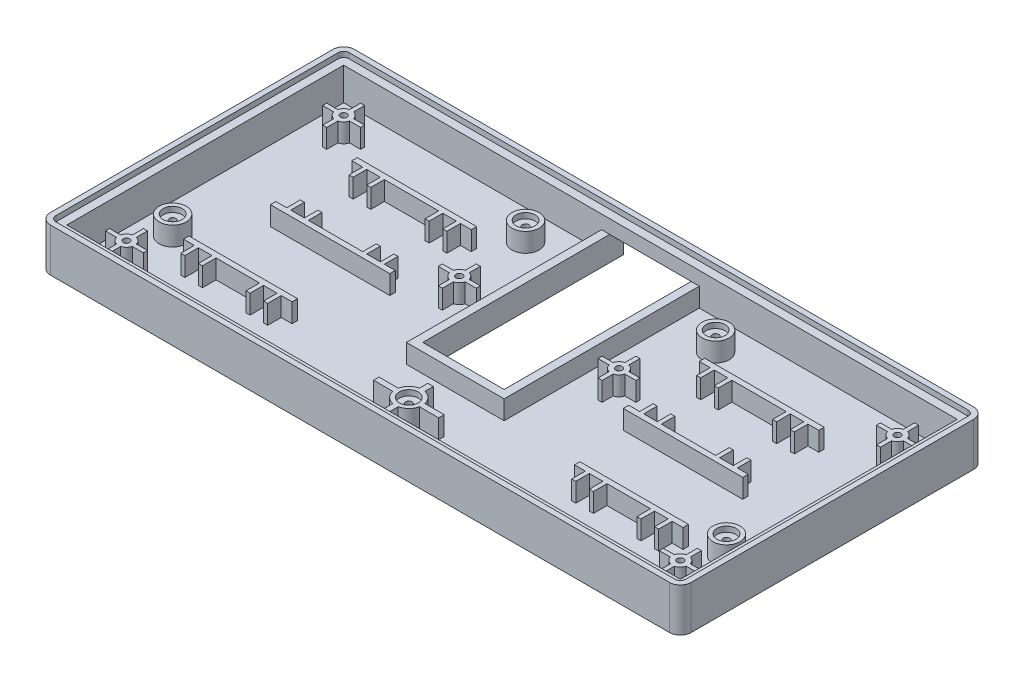
SolidWorks part; units mm, degrees
ref_plane "Front Plane" through (0, 0, 0) normal (0, 0, 1) x (1, 0, 0)
ref_plane "Top Plane" through (0, 0, 0) normal (0, 1, 0) x (1, 0, 0)
ref_plane "Right Plane" through (0, 0, 0) normal (1, 0, 0) x (0, 0, -1)
sketch "Sketch2" plane through (0, 0, 0) normal (0, 1, 0) x (1, 0, 0)
  line L0 (0, -55) -> (0, 55) construction
  line L1 (-118, 56) -> (118, 56)
  line L2 (-118, 56) -> (-118, -56)
  line L3 (-118, -56) -> (118, -56)
  line L4 (118, 56) -> (118, -56)
  line L5 (-55, 0) -> (55, 0) construction
  dimension "D1" = 236
  dimension "D2" = 112
  dimension "D3" = 118
  dimension "D4" = 56
extrude "Boss-Extrude1" add sketch "Sketch2" along normal blind 16
sketch "Sketch3" plane through (0, 16, 0) normal (0, 1, 0) x (1, 0, 0)
  line L0 (0, -55) -> (0, 55) construction
  line L1 (-113, 51) -> (113, 51)
  line L2 (-113, 51) -> (-113, -51)
  line L3 (-113, -51) -> (113, -51)
  line L4 (113, 51) -> (113, -51)
  line L5 (-9.35, 0) -> (9.35, 0) construction
  dimension "D1" = 102
  dimension "D2" = 226
  dimension "D3" = 113
  dimension "D4" = 51
extrude "PCB_case" cut sketch "Sketch3" against normal blind 14
sketch "Sketch4" plane through (0, 16, 0) normal (0, 1, 0) x (1, 0, 0)
  line L0 (-9.35, 0) -> (9.35, 0) construction
  line L1 (-116, 54) -> (116, 54)
  line L2 (-116, 54) -> (-116, -54)
  line L3 (-116, -54) -> (116, -54)
  line L4 (116, 54) -> (116, -54)
  line L5 (0, -8.8) -> (0, 8.8) construction
  dimension "D1" = 232
  dimension "D2" = 108
  dimension "D3" = 54
  dimension "D4" = 116
extrude "Upper_case" cut sketch "Sketch4" against normal blind 2
fillet "Fillet_Outside" radius 4 4 edges at (118, 8, -56) (-118, 8, -56) (-118, 8, 56) (118, 8, 56)
fillet "Fillet_inside_uplayer" radius 2 4 edges at (-116, 15, 54) (116, 15, 54) (116, 15, -54) (-116, 15, -54)
sketch "PCB_position" plane through (0, 0, 0) normal (0, 1, 0) x (1, 0, 0)
  line L1 (112, -50) -> (-112, -50)
  line L2 (112, -50) -> (112, 50)
  line L3 (112, 50) -> (-112, 50)
  line L4 (-112, -50) -> (-112, 50)
  line L5 (112, -50) -> (-112, 50) construction
  line L6 (112, 50) -> (-112, -50) construction
  point P0 (0, 0)
  dimension "D1" = 224
  dimension "D2" = 100
sketch "Ardino_pro_micro" plane through (0, 0, 0) normal (0, 1, 0) x (1, 0, 0)
  line L0 (0, -7.15) -> (0, 7.15) construction
  line L1 (-9, 25) -> (9, 25)
  line L2 (-9, 25) -> (-9, -11.9)
  line L3 (-9, -11.9) -> (9, -11.9)
  line L4 (9, 25) -> (9, -11.9)
  line L5 (112, 50) -> (-112, 50) construction
  dimension "D1" = 18
  dimension "D2" = 36.9
  dimension "D3" = 9
  dimension "D4" = 25
sketch "Sketch6" plane through (0, 0, 0) normal (0, 1, 0) x (1, 0, 0)
  circle A0 centre (0, -38) radius 5
  dimension "D1" = 10
extrude "Boss-Extrude2" add sketch "Sketch6" along normal blind 9
sketch "Sketch45" plane through (0, 0, 0) normal (0, 1, 0) x (1, 0, 0)
  line L0 (-12, -37) -> (-1, -37)
  line L1 (-1, -37) -> (-1, -30)
  line L2 (-1, -30) -> (1, -30)
  line L3 (1, -30) -> (1, -37)
  line L4 (1, -37) -> (12, -37)
  line L5 (12, -37) -> (12, -39)
  line L6 (12, -39) -> (1, -39)
  line L7 (1, -39) -> (1, -46)
  line L8 (1, -46) -> (-1, -46)
  line L9 (-1, -46) -> (-1, -39)
  line L10 (-1, -39) -> (-12, -39)
  line L11 (-12, -37) -> (-12, -39)
  line L12 (-12, -38) -> (12, -38) construction
  line L13 (0, -30) -> (0, -46) construction
  point P16 (0, -38)
  dimension "D1" = 2
  dimension "D2" = 2
  dimension "D3" = 8
  dimension "D4" = 12
extrude "Boss-Extrude6" add sketch "Sketch45" along normal blind 9
ref_plane "PCB_bot" through (0, 9, 0) normal (0, 1, 0) x (1, 0, 0)
sketch "Sketch27" plane through (0, 9, 0) normal (0, 1, 0) x (1, 0, 0)
  circle A0 centre (0, -38) radius 3.5
  dimension "D1" = 7
extrude "Cut-Extrude1" cut sketch "Sketch27" against normal blind 2
sketch "Sketch28" plane through (0, 0, 0) normal (0, 1, 0) x (1, 0, 0)
  line L0 (112, 50) -> (-112, 50) construction
  circle A0 centre (-35, 40) radius 5
  dimension "D1" = 10
  dimension "D2" = 10
extrude "Boss-Extrude3" add sketch "Sketch28" along normal blind 9
sketch "Sketch29" plane through (0, 9, 0) normal (0, 1, 0) x (1, 0, 0)
  circle A0 centre (-35, 40) radius 3.5
  dimension "D1" = 7
extrude "Cut-Extrude3" cut sketch "Sketch29" against normal blind 2
mirror "Mirror7" about plane through (0, 0, 0) normal (1, 0, 0) of "Cut-Extrude3", "Boss-Extrude3"
sketch "Sketch43" plane through (0, 0, 0) normal (0, 1, 0) x (1, 0, 0)
  point P0 (-35, 40)
  point P3 (35, 40)
  point P6 (0, -38)
hole_wizard "M2 Clearance Hole3" positions "Sketch43" profile "Sketch42" hole size "M2" standard "ANSI Metric" end condition through all
sketch "Sketch42" plane through (-35, 0, -40) normal (1, 0, 0) x (0, 0, -1)
  line L0 (0, 0) -> (0, 16)
  line L1 (0, 16) -> (1.2, 16)
  line L2 (1.2, 16) -> (1.2, 0)
  line L5 (1.2, 0) -> (0, 0)
  line L11 (0, -6.35) -> (0, 107.95) construction
  dimension "Thru Hole Dia." = 2.4
  dimension "Thru Hole Depth" = 16
sketch "Sketch44" plane through (0, 0, 0) normal (0, 1, 0) x (1, 0, 0)
  line L4 (-112, -50) -> (-112, 50) construction
  line L5 (112, -50) -> (-112, -50) construction
  circle A0 centre (-102, -23) radius 5
  dimension "D1" = 10
  dimension "D2" = 10
  dimension "D3" = 27
extrude "Boss-Extrude5" add sketch "Sketch44" along normal blind 9
sketch "Sketch46" plane through (0, 9, 0) normal (0, 1, 0) x (1, 0, 0)
  circle A0 centre (-102, -23) radius 3.5
  dimension "D1" = 7
extrude "Cut-Extrude6" cut sketch "Sketch46" against normal blind 2
sketch "Sketch49" plane through (0, 0, 0) normal (0, 1, 0) x (1, 0, 0)
  point P0 (-102, -23)
hole_wizard "M2 Clearance Hole4" positions "Sketch49" profile "Sketch48" hole size "M2" standard "ANSI Metric" end condition through all
sketch "Sketch48" plane through (-102, 0, 23) normal (1, 0, 0) x (0, 0, -1)
  line L0 (0, 0) -> (0, 16)
  line L1 (0, 16) -> (1.2, 16)
  line L2 (1.2, 16) -> (1.2, 0)
  line L5 (1.2, 0) -> (0, 0)
  line L11 (0, -6.35) -> (0, 107.95) construction
  dimension "Thru Hole Dia." = 2.4
  dimension "Thru Hole Depth" = 16
sketch "Sketch10" plane through (0, 0, 0) normal (0, 1, 0) x (1, 0, 0)
  line L0 (-86, 29) -> (-42, 29)
  line L1 (-42, 29) -> (-42, 27)
  line L3 (-86, 27) -> (-86, 29)
  line L4 (-74, 27) -> (-74, 22)
  line L5 (-74, 22) -> (-75.5, 22)
  line L6 (-75.5, 22) -> (-75.5, 27)
  line L8 (-54, 27) -> (-54, 22)
  line L9 (-54, 22) -> (-52.5, 22)
  line L10 (-52.5, 22) -> (-52.5, 27)
  line L11 (-47.5, 27) -> (-47.5, 22)
  line L12 (-47.5, 22) -> (-46, 22)
  line L13 (-46, 22) -> (-46, 27)
  line L14 (-80.5, 27) -> (-80.5, 22)
  line L15 (-80.5, 22) -> (-82, 22)
  line L16 (-82, 22) -> (-82, 27)
  line L18 (-112, -50) -> (-112, 50) construction
  line L25 (-86, 27) -> (-82, 27)
  line L26 (-80.5, 27) -> (-75.5, 27)
  line L27 (-74, 27) -> (-54, 27)
  line L28 (-52.5, 27) -> (-47.5, 27)
  line L29 (-46, 27) -> (-42, 27)
  line L30 (-75.5, 20) -> (-53.5, 20) construction
  dimension "D1" = 2
  dimension "D2" = 26
  dimension "D3" = 44
  dimension "D4" = 20
  dimension "D5" = 1.5
  dimension "D6" = 5
  dimension "D7" = 7
  dimension "D8" = 5
  dimension "D10" = 5
extrude "PCB_Sup1" add sketch "Sketch10" along normal blind 9
mirror "PCB_Sup2" about plane through (0, 0, 0) normal (1, 0, 0) of "PCB_Sup1"
sketch "Sketch16" plane through (0, 0, 0) normal (0, 1, 0) x (1, 0, 0)
  line L3 (-43, -2) -> (-87, -2)
  line L4 (-87, -2) -> (-87, 0)
  line L5 (-43, 0) -> (-43, -2)
  line L6 (-113, -51) -> (-113, 51) construction
  line L8 (-87, -1) -> (-43, -1) construction
  line L10 (-9.35, 0) -> (9.35, 0) construction
  line L11 (-83, 0) -> (-83, 5)
  line L12 (-83, 5) -> (-81.5, 5)
  line L13 (-81.5, 5) -> (-81.5, 0)
  line L14 (-76.5, 5) -> (-76.5, 0)
  line L15 (-76.5, 5) -> (-75, 5)
  line L16 (-75, 5) -> (-75, 0)
  line L17 (-55, 5) -> (-55, 0)
  line L18 (-53.5, 0) -> (-53.5, 5)
  line L19 (-53.5, 5) -> (-55, 5)
  line L20 (-47, 0) -> (-47, 5)
  line L21 (-47, 5) -> (-48.5, 5)
  line L22 (-48.5, 5) -> (-48.5, 0)
  line L25 (-87, 0) -> (-83, 0)
  line L26 (-81.5, 0) -> (-76.5, 0)
  line L27 (-75, 0) -> (-55, 0)
  line L28 (-53.5, 0) -> (-48.5, 0)
  line L29 (-47, 0) -> (-43, 0)
  point P4 (-87, -1)
  dimension "D1" = 2
  dimension "D2" = 5
  dimension "D3" = 5
  dimension "D4" = 5
  dimension "D5" = 20
  dimension "D6" = 1.5
  dimension "D7" = 1
  dimension "D8" = 44
  dimension "D9" = 26
extrude "PCB_Sup3" add sketch "Sketch16" along normal blind 9
mirror "PCB_Sup4" about plane through (0, 0, 0) normal (1, 0, 0) of "PCB_Sup3"
sketch "Sketch17" plane through (0, 0, 0) normal (0, 1, 0) x (1, 0, 0)
  line L0 (-92, -27) -> (-52, -27)
  line L1 (-52, -27) -> (-52, -29)
  line L2 (-52, -29) -> (-56, -29)
  line L3 (-56, -29) -> (-56, -34)
  line L4 (-56, -34) -> (-57.5, -34)
  line L5 (-57.5, -34) -> (-57.5, -29)
  line L6 (-57.5, -29) -> (-62.5, -29)
  line L7 (-62.5, -29) -> (-62.5, -34)
  line L8 (-62.5, -34) -> (-64, -34)
  line L9 (-64, -34) -> (-64, -29)
  line L10 (-64, -29) -> (-80, -29)
  line L11 (-80, -29) -> (-80, -34)
  line L12 (-80, -34) -> (-81.5, -34)
  line L13 (-81.5, -34) -> (-81.5, -29)
  line L14 (-81.5, -29) -> (-86.5, -29)
  line L15 (-86.5, -29) -> (-86.5, -34)
  line L16 (-86.5, -34) -> (-88, -34)
  line L17 (-88, -34) -> (-88, -29)
  line L18 (-88, -29) -> (-92, -29)
  line L19 (-92, -29) -> (-92, -27)
  line L21 (-112, -50) -> (-112, 50) construction
  line L22 (-92, -28) -> (-52, -28) construction
  line L23 (-9.35, 0) -> (9.35, 0) construction
  dimension "D1" = 2
  dimension "D2" = 1.5
  dimension "D3" = 4
  dimension "D4" = 5
  dimension "D5" = 5
  dimension "D6" = 4
  dimension "D7" = 5
  dimension "D8" = 28
  dimension "D9" = 40
  dimension "D10" = 20
extrude "PCB_Sup5" add sketch "Sketch17" along normal blind 9
mirror "PCB_Sup6" about plane through (0, 0, 0) normal (1, 0, 0) of "PCB_Sup5"
sketch "Sketch20" plane through (0, 0, 0) normal (0, 1, 0) x (1, 0, 0)
  line L0 (-13, 56) -> (-13, -21.9)
  line L1 (-13, -21.9) -> (-14, -21.9)
  line L3 (-14, -3.5) -> (-19, -3.5)
  line L4 (-19, -3.5) -> (-19, -2.5)
  line L5 (-19, -2.5) -> (-14, -2.5)
  line L6 (-14, -2.5) -> (-14, 2.5)
  line L7 (-14, 2.5) -> (-19, 2.5)
  line L8 (-19, 2.5) -> (-19, 3.5)
  line L9 (-19, 3.5) -> (-14, 3.5)
  line L10 (-14, 3.5) -> (-14, 45)
  line L11 (-14, 45) -> (-19, 45)
  line L12 (-19, 45) -> (-19, 46)
  line L13 (-19, 46) -> (-14, 46)
  line L14 (-14, 46) -> (-14, 51)
  line L15 (-14, 51) -> (-19, 51)
  line L16 (-19, 51) -> (-19, 52)
  line L17 (-19, 52) -> (-14, 52)
  line L18 (-14, 52) -> (-14, 56)
  line L19 (-14, 56) -> (-13, 56)
  line L20 (114, 56) -> (-114, 56) construction
  line L21 (-9, -11.9) -> (9, -11.9) construction
  line L26 (-14, -3.5) -> (-14, -10.9)
  line L27 (-14, -10.9) -> (-19, -10.9)
  line L28 (-19, -10.9) -> (-19, -11.9)
  line L29 (-19, -11.9) -> (-14, -11.9)
  line L30 (-14, -11.9) -> (-14, -16.9)
  line L31 (-14, -16.9) -> (-19, -16.9)
  line L32 (-19, -16.9) -> (-19, -17.9)
  line L33 (-19, -17.9) -> (-14, -17.9)
  line L34 (-14, -17.9) -> (-14, -21.9)
  line L35 (-9.35, 0) -> (9.35, 0) construction
  line L36 (-9, 25) -> (-9, -11.9) construction
  point P36 (-14, 0)
  dimension "D1" = 10
  dimension "D3" = 1
  dimension "D4" = 5
  dimension "D5" = 5
  dimension "D6" = 4
  dimension "D7" = 4
  dimension "D8" = 1
  dimension "D9" = 4
sketch "Sketch21" plane through (0, 0, 0) normal (0, 1, 0) x (1, 0, 0)
  line L4 (112, 50) -> (-112, 50) construction
  line L5 (-112, -50) -> (-112, 50) construction
  circle A0 centre (-102, 40) radius 3
  dimension "D1" = 6
  dimension "D2" = 10
  dimension "D3" = 10
extrude "TL_round" add sketch "Sketch21" along normal blind 9
sketch "Sketch22" plane through (0, 0, 0) normal (0, 1, 0) x (1, 0, 0)
  line L0 (-102.75, 47) -> (-102.75, 40.75)
  line L1 (-102.75, 47) -> (-101.25, 47)
  line L3 (-101.25, 33) -> (-102.75, 33)
  line L6 (-95, 40.75) -> (-95, 39.25)
  line L8 (-109, 39.25) -> (-109, 40.75)
  line L9 (-112.6968, 40) -> (-77.0407, 40) construction
  line L10 (-102, 65.5448) -> (-102, 28.4552) construction
  line L11 (-102.75, 40.75) -> (-109, 40.75)
  line L12 (-109, 39.25) -> (-102.75, 39.25)
  line L13 (-102.75, 39.25) -> (-102.75, 33)
  line L14 (-101.25, 33) -> (-101.25, 39.25)
  line L15 (-101.25, 39.25) -> (-95, 39.25)
  line L16 (-95, 40.75) -> (-101.25, 40.75)
  line L17 (-101.25, 40.75) -> (-101.25, 47)
  circle A2 centre (-102, 40) radius 3 construction
  point P15 (-102, 47)
  point P16 (-102, 40)
  point P20 (-109, 40)
  dimension "D1" = 1.5
  dimension "D2" = 1.5
  dimension "D3" = 14
  dimension "D4" = 14
  dimension "D5" = 7
  dimension "D6" = 7
extrude "TL_rect" add sketch "Sketch22" along normal blind 9
sketch "Sketch32" plane through (0, 9, 0) normal (0, 1, 0) x (1, 0, 0)
  point P0 (-102, 40)
hole_wizard "M2 Clearance Hole1" positions "Sketch32" profile "Sketch31" hole size "M2" standard "ANSI Metric" end condition through all
sketch "Sketch31" plane through (-102, 9, -40) normal (1, 0, 0) x (0, 0, 1)
  line L0 (0, 0) -> (0, 9)
  line L1 (0, 9) -> (1.2, 9)
  line L2 (1.2, 9) -> (1.2, 0)
  line L5 (1.2, 0) -> (0, 0)
  line L11 (0, -6.35) -> (0, 107.95) construction
  dimension "Thru Hole Dia." = 2.4
  dimension "Thru Hole Depth" = 9
mirror "Mirror8" about plane through (0, 0, 0) normal (1, 0, 0) of "M2 Clearance Hole1", "TL_rect", "TL_round"
mirror "Mirror9" about plane through (0, 0, 0) normal (0, 0, 1) of "Mirror8", "TL_round", "TL_rect", "M2 Clearance Hole1"
sketch "Sketch36" plane through (0, 0, 0) normal (0, 1, 0) x (1, 0, 0)
  line L2 (-9.35, 0) -> (9.35, 0) construction
  circle A0 centre (-29.413, 10) radius 3
  dimension "D2" = 6
  dimension "D1" = 10
extrude "CL_round" add sketch "Sketch36" along normal blind 9
sketch "Sketch37" plane through (0, 0, 0) normal (0, 1, 0) x (1, 0, 0)
  line L0 (-30.163, 17) -> (-30.163, 10.75)
  line L1 (-30.163, 17) -> (-28.663, 17)
  line L2 (-28.663, 3) -> (-30.163, 3)
  line L3 (-22.413, 10.75) -> (-22.413, 9.25)
  line L4 (-36.413, 9.25) -> (-36.413, 10.75)
  line L5 (-30.163, 10.75) -> (-36.413, 10.75)
  line L6 (-36.413, 9.25) -> (-30.163, 9.25)
  line L7 (-30.163, 9.25) -> (-30.163, 3)
  line L8 (-28.663, 3) -> (-28.663, 9.25)
  line L9 (-28.663, 9.25) -> (-22.413, 9.25)
  line L10 (-22.413, 10.75) -> (-28.663, 10.75)
  line L11 (-28.663, 10.75) -> (-28.663, 17)
  line L12 (-36.413, 10) -> (-22.413, 10) construction
  line L13 (-29.413, 17) -> (-29.413, 3) construction
  circle A1 centre (-29.413, 10) radius 3 construction
  point P11 (-29.413, 10)
  dimension "D1" = 1.5
  dimension "D2" = 14
  dimension "D3" = 1.5
  dimension "D4" = 14
  dimension "D5" = 7
  dimension "D6" = 7
extrude "CL_rect" add sketch "Sketch37" along normal blind 9
sketch "Sketch40" plane through (0, 9, 0) normal (0, 1, 0) x (1, 0, 0)
  point P0 (-29.413, 10)
hole_wizard "M2 Clearance Hole2" positions "Sketch40" profile "Sketch39" hole size "M2" standard "ANSI Metric" end condition through all
sketch "Sketch39" plane through (-29.413, 9, -10) normal (1, 0, 0) x (0, 0, 1)
  line L0 (0, 0) -> (0, 9)
  line L1 (0, 9) -> (1.2, 9)
  line L2 (1.2, 9) -> (1.2, 0)
  line L5 (1.2, 0) -> (0, 0)
  line L11 (0, -6.35) -> (0, 107.95) construction
  dimension "Thru Hole Dia." = 2.4
  dimension "Thru Hole Depth" = 9
sketch "Sketch33" plane through (0, 0, 0) normal (0, 1, 0) x (1, 0, 0)
  line L0 (114, 56) -> (-114, 56) construction
  line L1 (-18, 56) -> (18, 56)
  line L2 (-18, 56) -> (-18, -20.9)
  line L3 (-18, -20.9) -> (18, -20.9)
  line L4 (18, 56) -> (18, -20.9)
  line L5 (-9, 25) -> (-9, -11.9) construction
  line L6 (9, 25) -> (9, -11.9) construction
  line L7 (-9, -11.9) -> (9, -11.9) construction
  dimension "D1" = 9
  dimension "D2" = 9
  dimension "D3" = 9
extrude "Boss-Extrude4" add sketch "Sketch33" along normal blind 9
sketch "Sketch34" plane through (0, 9, 0) normal (0, 1, 0) x (1, 0, 0)
  line L0 (114, 56) -> (-114, 56) construction
  line L1 (-15, 56) -> (15, 56)
  line L2 (-15, 56) -> (-15, -17.9)
  line L3 (-15, -17.9) -> (15, -17.9)
  line L4 (15, 56) -> (15, -17.9)
  line L5 (-18, -20.9) -> (-18, 51) construction
  line L6 (18, -20.9) -> (18, 51) construction
  line L7 (18, -20.9) -> (-18, -20.9) construction
  dimension "D1" = 3
  dimension "D2" = 3
  dimension "D3" = 3
extrude "Cut-Extrude5" cut sketch "Sketch34" against normal blind 9
mirror "Mirror10" about plane through (0, 0, 0) normal (1, 0, 0) of "M2 Clearance Hole2", "CL_rect", "CL_round"
mirror "Mirror11" about plane through (0, 0, 0) normal (1, 0, 0) of "Boss-Extrude5", "Cut-Extrude6", "M2 Clearance Hole4"
